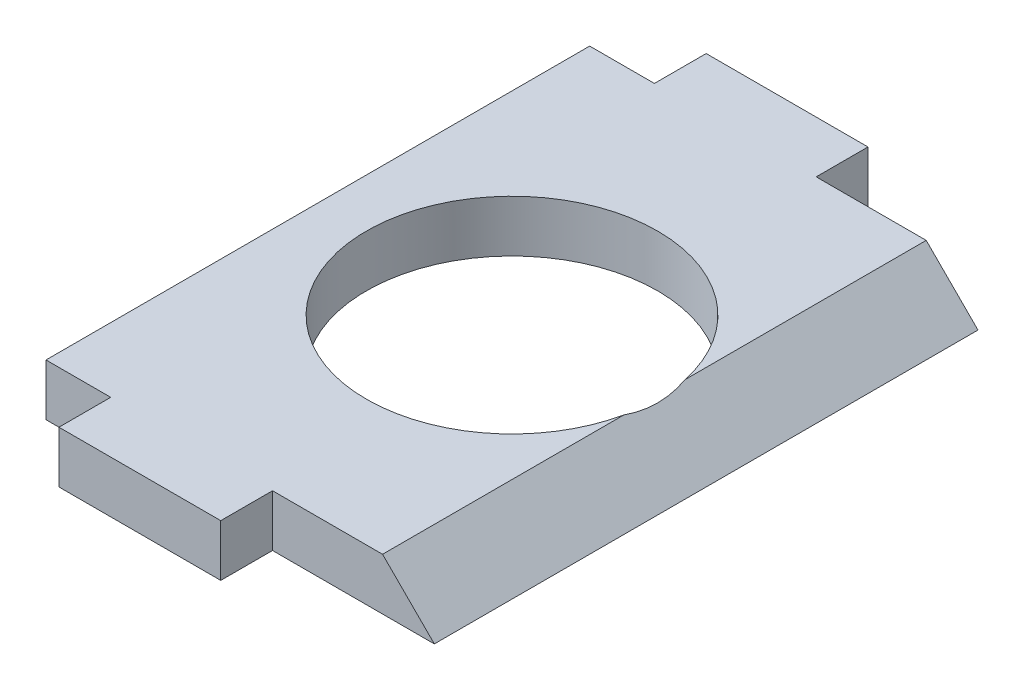
SolidWorks part; units mm, degrees
ref_plane "Front Plane" through (0, 0, 0) normal (0, 0, 1) x (1, 0, 0)
ref_plane "Top Plane" through (0, 0, 0) normal (0, 1, 0) x (1, 0, 0)
ref_plane "Right Plane" through (0, 0, 0) normal (1, 0, 0) x (0, 0, -1)
sketch "Sketch1" plane through (0, 0, 0) normal (0, 1, 0) x (1, 0, 0)
  line L0 (35, 0) -> (35, 8)
  line L1 (0, 0) -> (60, 0)
  line L2 (0, 0) -> (0, 100)
  line L3 (0, 100) -> (60, 100)
  line L4 (60, 0) -> (60, 100)
  line L5 (35, 8) -> (60, 8)
  line L6 (60, 50) -> (0, 50) construction
  line L7 (35, 100) -> (35, 92)
  line L8 (35, 92) -> (60, 92)
  line L9 (0, 92) -> (10, 92)
  line L10 (10, 92) -> (10, 100)
  line L11 (0, 8) -> (10, 8)
  line L12 (10, 8) -> (10, 0)
  circle A0 centre (30, 50) radius 22.5
  dimension "D7" = 45
  dimension "D1" = 100
  dimension "D2" = 60
  dimension "D3" = 8
  dimension "D4" = 25
  dimension "D5" = 10
  dimension "D6" = 8
extrude "Boss-Extrude1" add sketch "Sketch1" along normal blind 8
sketch "Sketch7" plane through (0, 0, -8) normal (0, 0, 1) x (1, 0, 0)
  line L0 (60, 0) -> (52, 8)
  line L1 (35, 8) -> (60, 8) construction
  line L2 (52, 8) -> (60, 8)
  line L3 (60, 8) -> (60, 0)
  dimension "D1" = 45
extrude "Cut-Extrude4" cut sketch "Sketch7" against normal through all
